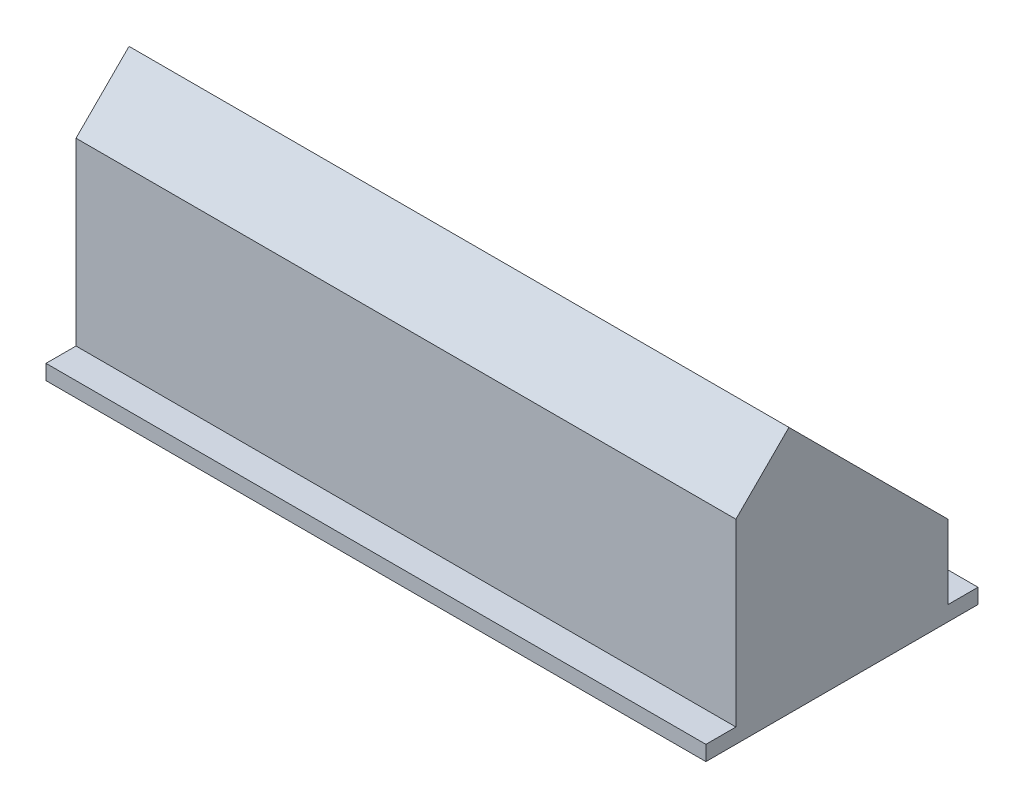
SolidWorks part; units mm, degrees
ref_plane "Front Plane" through (0, 0, 0) normal (0, 0, 1) x (1, 0, 0)
ref_plane "Top Plane" through (0, 0, 0) normal (0, 1, 0) x (1, 0, 0)
ref_plane "Right Plane" through (0, 0, 0) normal (1, 0, 0) x (0, 0, -1)
sketch "Sketch2" plane through (0, 0, 0) normal (1, 0, 0) x (0, 0, -1)
  line L0 (0, 46.0731) -> (0, -47.1242) construction
  line L1 (-53.0804, 0) -> (53.7812, 0) construction
  line L4 (25, -30) -> (25, -5.3553)
  line L5 (25, -5.3553) -> (-28.033, 47.6777)
  line L6 (-28.033, 47.6777) -> (-45.7107, 30)
  line L8 (-45.7107, 30) -> (-45.7107, -30)
  line L11 (-45.7107, -35) -> (25, -35)
  line L12 (-45.7107, -35) -> (-55.7107, -35)
  line L13 (-55.7107, -35) -> (-55.7107, -30)
  line L14 (-55.7107, -30) -> (-45.7107, -30)
  line L15 (-45.7107, -30) -> (-45.7107, -35) construction
  line L16 (25, -30) -> (35, -30)
  line L17 (35, -30) -> (35, -35)
  line L18 (35, -35) -> (25, -35)
  line L19 (25, -35) -> (25, -30) construction
  point P5 (-45.7107, 0)
  dimension "D1" = 75
  dimension "D2" = 45
  dimension "D3" = 5
  dimension "D4" = 25
  dimension "D5" = 65
  dimension "D6" = 90
  dimension "D7" = 10
  dimension "D8" = 10
extrude "Boss-Extrude1" add sketch "Sketch2" along normal mid plane 220
shell "Shell1" thickness 2
sketch "Sketch3" plane through (0, -33, 0) normal (0, 1, 0) x (1, 0, 0)
  line L1 (-108, -23) -> (108, -23)
  line L2 (-108, -23) -> (-108, 23)
  line L3 (-108, 23) -> (108, 23)
  line L12 (108, -23) -> (108, 23)
  line L13 (-108, -23) -> (108, 23) construction
  line L14 (-108, 23) -> (108, -23) construction
  point P0 (0, 0)
extrude "Cut-Extrude1" cut sketch "Sketch3" against normal blind 10
sketch "Sketch5" plane through (-108, 0, 0) normal (1, 0, 0) x (0, 0, -1)
  line L10 (23, -32) -> (23, -3.3553) construction
  line L13 (-36.4411, 36.4411) -> (23, -23)
  line L16 (23, -23) -> (23, -4.8981)
  line L17 (-26.6188, 46.2635) -> (-43.7107, 29.1716) construction
  line L20 (23, -4.8981) -> (17.4846, -10.4135)
  line L21 (17.4846, -10.4135) -> (-32.9056, 39.9767)
  line L22 (-32.9056, 39.9767) -> (-36.4411, 36.4411)
  point P1 (0, 0)
  point P12 (-34.0802, 41.302)
  point P13 (23, -22.2816)
  point P15 (0, 0)
  point P17 (0, 0)
  dimension "D1" = 5
  dimension "D2" = 7.8
extrude "Boss-Extrude2" add sketch "Sketch5" along normal up to surface (216 mm away)
sketch "Sketch6" plane through (0, 3.5355, -3.5355) normal (0, 0.7071, -0.7071) x (1, 0, 0)
  line L0 (-108, 13.636) -> (-98, 13.636)
  line L1 (-108, -16.4497) -> (108, -16.4497) construction
  line L2 (108, 18.636) -> (-108, 18.636) construction
  line L4 (-5, 18.636) -> (-98, 18.636)
  line L6 (0, 0) -> (0, 56.69) construction
  line L8 (-98, 13.636) -> (-98, 18.636)
  line L9 (-108, 13.636) -> (-108, 3.5503)
  line L11 (-108, 3.5503) -> (108, 3.5503) construction
  line L14 (108, 3.5503) -> (108, 13.636)
  line L15 (108, 18.636) -> (108, -51.5355) construction
  line L16 (108, 13.636) -> (98, 13.636)
  line L17 (98, 13.636) -> (98, 18.636)
  line L18 (98, 18.636) -> (5, 18.636)
  line L19 (5, 18.636) -> (5, 13.636)
  line L24 (5, 13.636) -> (-5, 13.636)
  line L25 (-5, 18.636) -> (-5, 13.636)
  line L40 (-108, 18.636) -> (-108, -51.5355) construction
  line L41 (108, -51.5355) -> (108, 19.7269) construction
  line L42 (108, -36.4497) -> (108, -46.5355)
  line L43 (108, -46.5355) -> (98, -46.5355)
  line L44 (98, -46.5355) -> (98, -51.5355)
  line L45 (98, -51.5355) -> (5, -51.5355)
  line L46 (5, -51.5355) -> (5, -46.5355)
  line L47 (-5, -51.5355) -> (-5, -46.5355)
  line L48 (5, -46.5355) -> (-5, -46.5355)
  line L49 (-5, -51.5355) -> (-98, -51.5355)
  line L50 (-98, -46.5355) -> (-98, -51.5355)
  line L51 (-108, -46.5355) -> (-98, -46.5355)
  line L52 (-108, -46.5355) -> (-108, -36.4497)
  line L53 (-108, -36.4497) -> (108, -36.4497) construction
  line L54 (-108, 3.5503) -> (-108, -36.4497)
  line L55 (108, 3.5503) -> (108, -36.4497)
  circle A0 centre (0, 16.136) radius 1.5
  circle A5 centre (-102.5, 16.136) radius 1.5
  circle A7 centre (102.5, 16.136) radius 1.5
  circle A8 centre (102.5, -49.0355) radius 1.5
  circle A9 centre (0, -49.0355) radius 1.5
  circle A10 centre (-102.5, -49.0355) radius 1.5
  dimension "D1" = 3
  dimension "D5" = 5
  dimension "D6" = 5
  dimension "D4" = 10
  dimension "D2" = 20
  dimension "D3" = 102.5
  dimension "D7" = 10
  dimension "D8" = 2.5
extrude "Cut-Extrude2" cut sketch "Sketch6" along normal mid plane 10
sketch "Sketch7" plane through (0, -30, 0) normal (0, 1, 0) x (1, 0, 0)
  line L0 (0, 52.4159) -> (0, -72.4611) construction
  line L1 (110, 35) -> (-110, 35) construction
  line L2 (-110, 35) -> (-110, 25) construction
  circle A0 centre (-105, 30) radius 2.25
  dimension "D1" = 4.5
  dimension "D2" = 5
  dimension "D3" = 5
